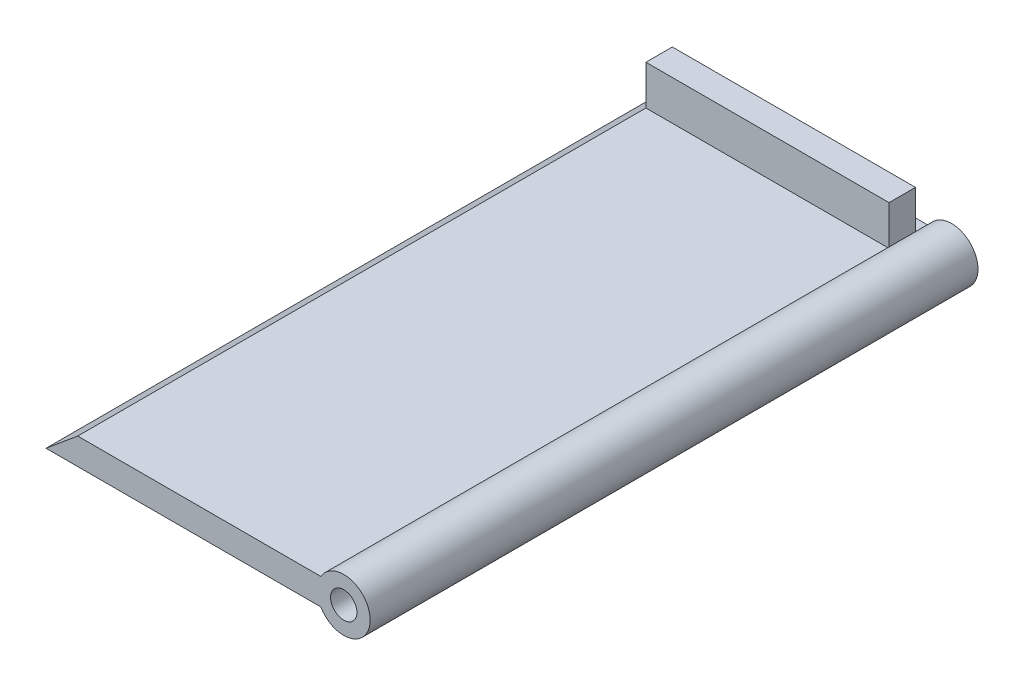
SolidWorks part; units mm, degrees
ref_plane "Front Plane" through (0, 0, 0) normal (0, 0, 1) x (1, 0, 0)
ref_plane "Top Plane" through (0, 0, 0) normal (0, 1, 0) x (1, 0, 0)
ref_plane "Right Plane" through (0, 0, 0) normal (1, 0, 0) x (0, 0, -1)
sketch "Sketch1" plane through (0, 0, 0) normal (0, 0, 1) x (1, 0, 0)
  line L0 (-33.2433, 2.8152) -> (-25.6233, -3.5348)
  line L1 (32.7967, 2.8152) -> (-33.2433, 2.8152)
  line L3 (32.7967, -3.5348) -> (-25.6233, -3.5348)
  arc A0 (32.7967, -3.5348) -> (32.7967, 2.8152) centre (38.296, -0.3598) ccw
  circle A1 centre (38.296, -0.3598) radius 3.175
  dimension "D1" = 12.7
  dimension "D2" = 6.35
  dimension "D5" = 6.35
extrude "Boss-Extrude1" add sketch "Sketch1" along normal blind 146.05
ref_plane "Plane1" through (0, 0, 3.175) normal (0, 0, 1) x (1, 0, 0)
sketch "Sketch2" plane through (0, 0, 3.175) normal (0, 0, 1) x (1, 0, 0)
  line L0 (-22.4483, 2.8152) -> (-25.6233, 2.8152)
  line L1 (32.7967, 2.8152) -> (29.6217, 2.8152)
  line L2 (32.7967, 2.8152) -> (32.7967, 12.3402)
  line L3 (32.7967, 12.3402) -> (-25.6233, 12.3402)
  line L4 (-25.6233, 2.8152) -> (-25.6233, 12.3402)
  line L5 (32.7967, 2.8152) -> (-33.2433, 2.8152) construction
  line L6 (29.6217, 2.8152) -> (29.6217, 9.1652)
  line L7 (29.6217, 9.1652) -> (-22.4483, 9.1652)
  line L8 (-22.4483, 2.8152) -> (-22.4483, 9.1652)
  dimension "D1" = 3.175
  dimension "D2" = 3.175
  dimension "D3" = 3.175
  dimension "D4" = 6.35
  dimension "D5" = 58.42
extrude "Boss-Extrude2" add sketch "Sketch2" along normal blind 3.175
ref_plane "Plane2" through (0, 0, 6.35) normal (0, 0, 1) x (1, 0, 0)
sketch "Sketch3" plane through (0, 0, 6.35) normal (0, 0, 1) x (1, 0, 0)
  line L1 (-25.6233, 12.3402) -> (32.7967, 12.3402)
  line L2 (-25.6233, 12.3402) -> (-25.6233, 2.8152)
  line L3 (-25.6233, 2.8152) -> (32.7967, 2.8152)
  line L4 (32.7967, 12.3402) -> (32.7967, 2.8152)
extrude "Boss-Extrude3" add sketch "Sketch3" along normal blind 3.175
sketch "Sketch4" plane through (0, 0, 146.05) normal (0, 0, 1) x (1, 0, 0)
  line L0 (-33.2433, 2.8152) -> (-33.2433, -3.5348)
  line L1 (-33.2433, -3.5348) -> (-25.6233, -3.5348)
  line L2 (-25.6233, -3.5348) -> (-33.2433, 2.8152)
extrude "Boss-Extrude4" add sketch "Sketch4" against normal blind 146.05
sketch "Sketch5" plane through (0, 0, 146.05) normal (0, 0, 1) x (1, 0, 0)
  line L0 (-33.2433, -3.5348) -> (-25.6233, 2.8152)
  line L1 (32.7967, 2.8152) -> (-33.2433, 2.8152) construction
  line L2 (-25.6233, 2.8152) -> (-33.2433, 2.8152)
  line L3 (-33.2433, 2.8152) -> (-33.2433, -3.5348)
  line L4 (32.7967, 2.8152) -> (32.7967, 12.3402) construction
  dimension "D1" = 58.42
extrude "Cut-Extrude1" cut sketch "Sketch5" against normal blind 146.05
